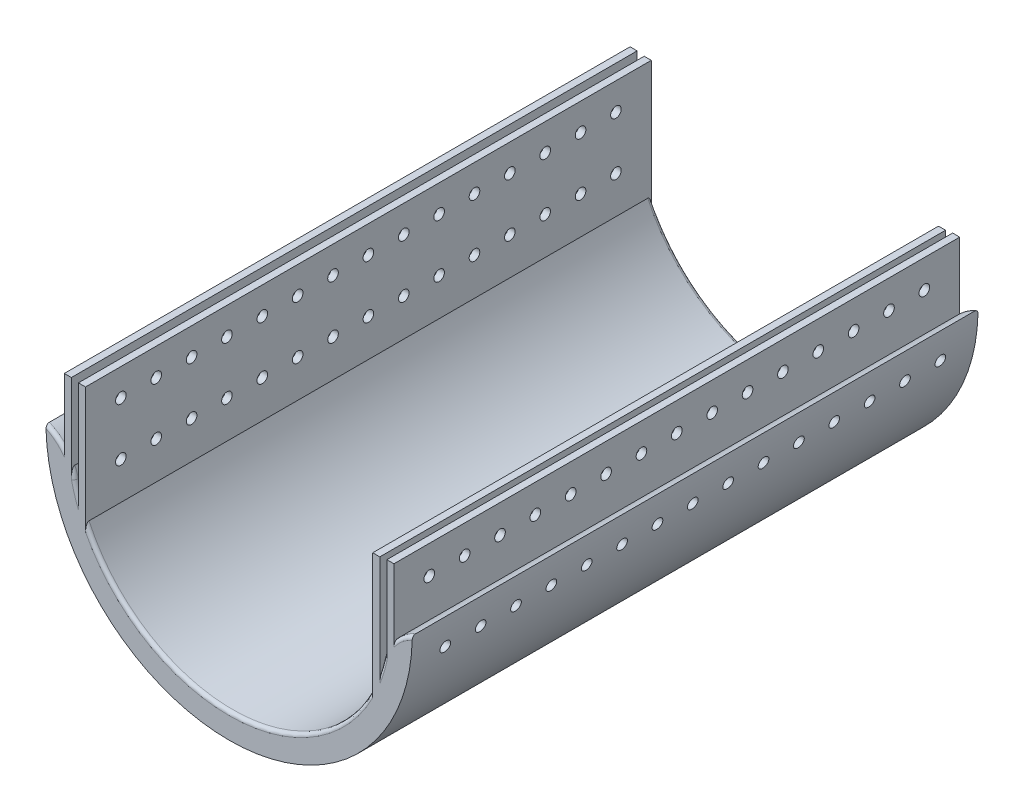
SolidWorks part; units mm, degrees
ref_plane "Front Plane" through (0, 0, 0) normal (0, 0, 1) x (1, 0, 0)
ref_plane "Top Plane" through (0, 0, 0) normal (0, 1, 0) x (1, 0, 0)
ref_plane "Right Plane" through (0, 0, 0) normal (1, 0, 0) x (0, 0, -1)
sketch "Sketch1" plane through (0, 0, 0) normal (0, 0, 1) x (1, 0, 0)
  arc A18 (51.7991, -0.2994) -> (43.6352, -10.0449) centre (57.2847, -13.187) ccw
  arc A19 (-43.6352, -10.0449) -> (43.6352, -10.0449) centre (0, 0) ccw
  arc A20 (-51.7991, -0.2994) -> (51.7991, -0.2994) centre (0, 0) ccw
  arc A21 (-43.6352, -10.0449) -> (-51.7991, -0.2994) centre (-57.2847, -13.187) ccw
extrude "Boss-Extrude1" add sketch "Sketch1" along normal blind 160
fillet "Fillet1" radius 1 6 edges at (46.5478, -4.1925, 160) (-46.5478, -4.1925, 160) (46.5478, -4.1925, 0) (-46.5478, -4.1925, 0) (0, -44.7764, 160) (0, -44.7764, 0)
sketch "Sketch2" plane through (0, 0, 160) normal (0, 0, 1) x (1, 0, 0)
  line L0 (0, 0) -> (0, -62.6998) construction
  line L1 (-44.6097, -10.2692) -> (-46.6097, -10.2692)
  line L2 (-44.6097, -10.2692) -> (-44.6097, 14.7308)
  line L3 (-44.6097, 14.7308) -> (-46.6097, 14.7308)
  line L4 (-46.6097, -10.2692) -> (-46.6097, 14.7308)
  line L5 (46.6097, -10.2692) -> (46.6097, 14.7308)
  line L6 (44.6097, 14.7308) -> (46.6097, 14.7308)
  line L7 (44.6097, -10.2692) -> (44.6097, 14.7308)
  line L8 (44.6097, -10.2692) -> (46.6097, -10.2692)
  line L9 (40.6097, -21.1266) -> (42.6097, -21.1266)
  line L10 (-40.6097, -21.1266) -> (-42.6097, -21.1266)
  line L11 (-40.6097, -21.1266) -> (-40.6097, 14.4195)
  line L12 (-40.6097, 14.4195) -> (-42.6097, 14.4195)
  line L13 (-42.6097, -21.1266) -> (-42.6097, 14.4195)
  line L14 (42.6097, -21.1266) -> (42.6097, 14.4195)
  line L15 (40.6097, 14.4195) -> (42.6097, 14.4195)
  line L16 (40.6097, -21.1266) -> (40.6097, 14.4195)
  arc A0 (-44.6097, -10.2692) -> (44.6097, -10.2692) centre (0, 0) ccw construction
  dimension "D1" = 25
  dimension "D2" = 2
  dimension "D3" = 2
  dimension "D4" = 2
extrude "Boss-Extrude2" add sketch "Sketch2" against normal blind 160
sketch "Sketch3" plane through (46.6097, 0, 0) normal (1, 0, 0) x (0, 0, -1)
  line L0 (-150, 14.7308) -> (-150, -0.2994) construction
  line L1 (0, 14.7308) -> (-160, 14.7308) construction
  circle A0 centre (-150, 6.7308) radius 1.5
  circle A1 centre (-150, -8.2692) radius 1.5
  circle A2 centre (-140, 6.7308) radius 1.5
  circle A3 centre (-140, -8.2692) radius 1.5
  circle A4 centre (-130, 6.7308) radius 1.5
  circle A5 centre (-130, -8.2692) radius 1.5
  circle A6 centre (-120, 6.7308) radius 1.5
  circle A7 centre (-120, -8.2692) radius 1.5
  circle A8 centre (-110, 6.7308) radius 1.5
  circle A9 centre (-110, -8.2692) radius 1.5
  circle A10 centre (-100, 6.7308) radius 1.5
  circle A11 centre (-100, -8.2692) radius 1.5
  circle A12 centre (-90, 6.7308) radius 1.5
  circle A13 centre (-90, -8.2692) radius 1.5
  circle A14 centre (-80, 6.7308) radius 1.5
  circle A15 centre (-80, -8.2692) radius 1.5
  circle A16 centre (-70, 6.7308) radius 1.5
  circle A17 centre (-70, -8.2692) radius 1.5
  circle A18 centre (-60, 6.7308) radius 1.5
  circle A19 centre (-60, -8.2692) radius 1.5
  circle A20 centre (-50, 6.7308) radius 1.5
  circle A21 centre (-50, -8.2692) radius 1.5
  circle A22 centre (-40, 6.7308) radius 1.5
  circle A23 centre (-40, -8.2692) radius 1.5
  circle A24 centre (-30, 6.7308) radius 1.5
  circle A25 centre (-30, -8.2692) radius 1.5
  circle A26 centre (-20, 6.7308) radius 1.5
  circle A27 centre (-20, -8.2692) radius 1.5
  circle A28 centre (-10, 6.7308) radius 1.5
  circle A29 centre (-10, -8.2692) radius 1.5
  spline S0 degree 1 poles (-159, -0.2994) (-1, -0.2994) knots 0 0 1 1 construction
  dimension "D1" = 3
  dimension "D2" = 3
  dimension "D3" = 8
  dimension "D4" = 15
  dimension "D5" = 15
extrude "Cut-Extrude1" cut sketch "Sketch3" against normal through all both and the other way through all
